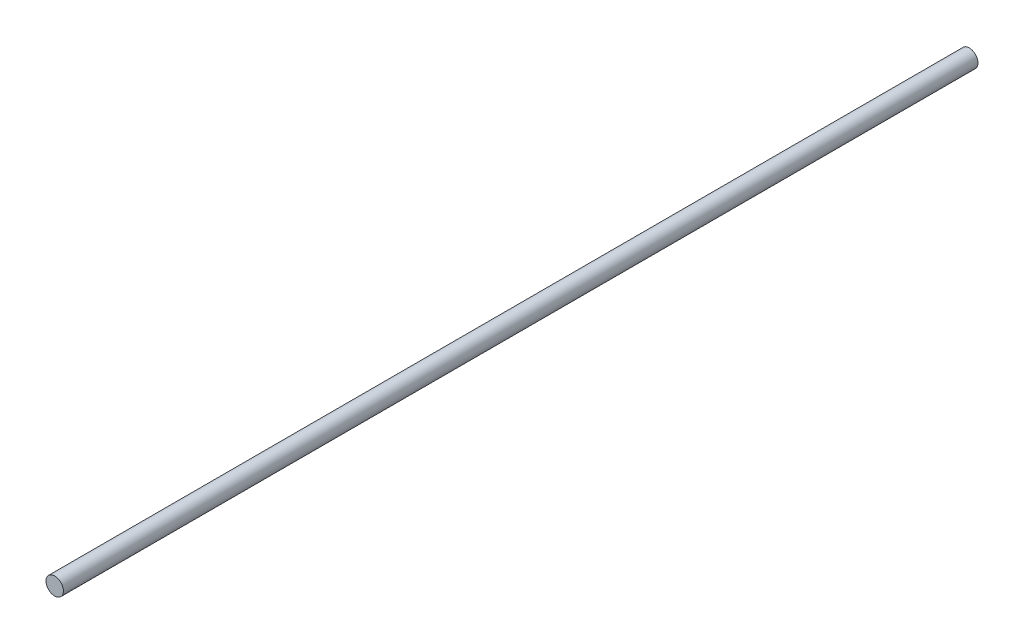
SolidWorks part; units mm, degrees
material "Hexcel AS4C (3000 Filaments)"
ref_plane "Front Plane" through (0, 0, 0) normal (0, 0, 1) x (1, 0, 0)
ref_plane "Top Plane" through (0, 0, 0) normal (0, 1, 0) x (1, 0, 0)
ref_plane "Right Plane" through (0, 0, 0) normal (1, 0, 0) x (0, 0, -1)
sketch "Sketch1" plane through (0, 0, 0) normal (0, 0, 1) x (1, 0, 0)
  circle A0 centre (0, 0) radius 1
  dimension "D1" = 2
extrude "Boss-Extrude1" add sketch "Sketch1" along normal blind 105
